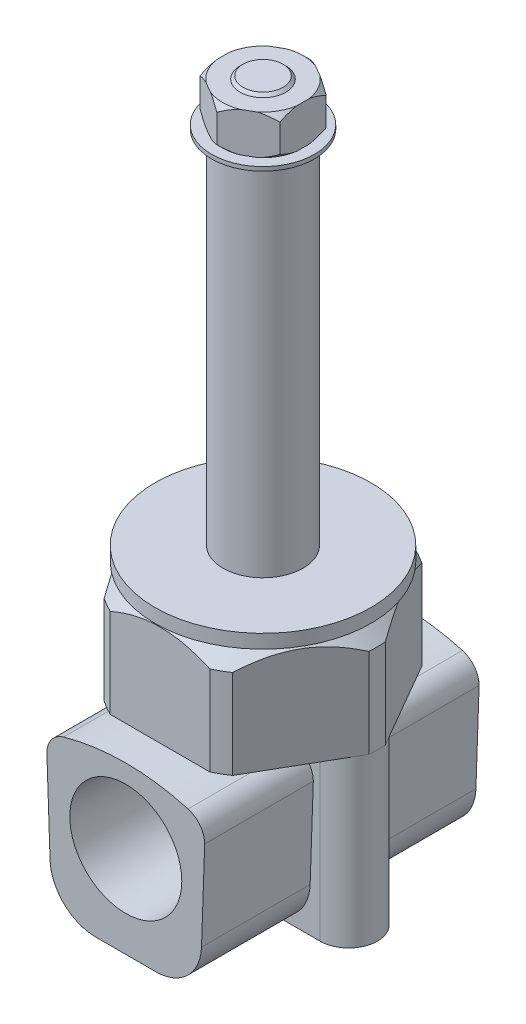
SolidWorks part; units mm, degrees
ref_plane "Front" through (0, 0, 0) normal (0, 0, 1) x (1, 0, 0)
ref_plane "Top" through (0, 0, 0) normal (0, 1, 0) x (1, 0, 0)
ref_plane "Right" through (0, 0, 0) normal (1, 0, 0) x (0, 0, -1)
sketch "Sketch1" plane through (0, 0, 0) normal (0, 1, 0) x (1, 0, 0)
  line L1 (-9.9737, -0.7251) -> (-5.6148, -8.2749)
  line L2 (-4.3589, -9) -> (4.3589, -9)
  line L3 (5.6148, -8.2749) -> (9.9737, -0.7251)
  line L4 (9.9737, 0.7251) -> (5.6148, 8.2749)
  line L5 (4.3589, 9) -> (-4.3589, 9)
  line L6 (-5.6148, 8.2749) -> (-9.9737, 0.7251)
  circle A0 centre (0, 0) radius 9 construction
  arc A1 (-4.3589, 9) -> (-5.6148, 8.2749) centre (0, 0) ccw
  arc A2 (-9.9737, 0.7251) -> (-9.9737, -0.7251) centre (0, 0) ccw
  arc A3 (-5.6148, -8.2749) -> (-4.3589, -9) centre (0, 0) ccw
  arc A4 (4.3589, -9) -> (5.6148, -8.2749) centre (0, 0) ccw
  arc A5 (9.9737, -0.7251) -> (9.9737, 0.7251) centre (0, 0) ccw
  arc A6 (5.6148, 8.2749) -> (4.3589, 9) centre (0, 0) ccw
  dimension "D1" = 18
  dimension "D2" = 20
extrude "Base Nut Extrude" add sketch "Sketch1" along normal blind 9.3
sketch "Sketch2" plane through (0, 0, 0) normal (0, 0, 1) x (1, 0, 0)
  line L0 (-9.9737, 9.3) -> (-5.6148, 9.3) construction
  line L1 (-9.9737, 9.3) -> (-10, 9.3) construction
  line L2 (-10, 9.3) -> (-10, 0) construction
  line L3 (-9.9737, 9.3) -> (-8.5, 9.3)
  line L4 (-9.9737, 9.3) -> (-10, 9.3)
  line L5 (-10, 9.3) -> (-10, 7.8)
  line L6 (-10, 7.8) -> (-8.5, 9.3)
  dimension "D1" = 1.5
  dimension "D2" = 1.5
ref_axis "Axis1" through (0, 49.0775, 0) along (0, -1, 0)
revolve "Nut Detail" cut sketch "Sketch2" angle 360 about axis through (0, 49.0775, 0) along (0, -1, 0)
sketch "Sketch3" plane through (0, 9.3, 0) normal (0, 1, 0) x (1, 0, 0)
  circle A0 centre (0, 0) radius 9.45
  dimension "D1" = 18.9
extrude "Coil Base" add sketch "Sketch3" along normal blind 1.2
sketch "Sketch4" plane through (0, 10.5, 0) normal (0, 1, 0) x (1, 0, 0)
  circle A0 centre (0, 0) radius 3.5
  dimension "D1" = 7
extrude "Inner Cylinder" add sketch "Sketch4" along normal blind 31.5
sketch "Sketch5" plane through (0, 42, 0) normal (0, 1, 0) x (1, 0, 0)
  circle A0 centre (0, 0) radius 4.5
  dimension "D1" = 9
extrude "Washer" add sketch "Sketch5" along normal blind 0.35
sketch "Sketch6" plane through (0, 42.35, 0) normal (0, 1, 0) x (1, 0, 0)
  circle A0 centre (0, 0) radius 2
  dimension "D1" = 4
extrude "Mounting Thread" add sketch "Sketch6" along normal blind 3.7
chamfer "Thread Chamfer" distance 0.25 1 edges at (0, 46.05, 2)
sketch "Sketch7" plane through (0, 0, 0) normal (0, -1, 0) x (1, 0, 0)
  line L0 (-7.5, 0) -> (7.5, 0) construction
  line L1 (-7.5, 2.5) -> (7.5, 2.5)
  line L3 (7.5, -2.5) -> (-7.5, -2.5)
  arc A0 (-7.5, 2.5) -> (-7.5, -2.5) centre (-7.5, 0) ccw
  arc A1 (7.5, -2.5) -> (7.5, 2.5) centre (7.5, 0) ccw
  point P4 (0, 0)
  dimension "D2" = 5
  dimension "D1" = 15
extrude "Port Base" add sketch "Sketch7" along normal blind 14.5
sketch "Sketch8" plane through (0, 0, 2.5) normal (0, 0, 1) x (1, 0, 0)
  line L0 (7.5, 0) -> (-7.5, 0) construction
  line L1 (-6.9, -2.6798) -> (-6.622, -10.6396)
  line L2 (-6.9, -2.6798) -> (-6.9, -10.5) construction
  line L3 (2.6245, -14.5) -> (-2.6245, -14.5)
  line L4 (6.9, -2.6798) -> (6.9, -10.5) construction
  line L5 (7.5, -14.5) -> (-7.5, -14.5) construction
  line L6 (6.9, -2.6798) -> (6.622, -10.6396)
  arc A0 (-6.622, -10.6396) -> (-2.6245, -14.5) centre (-2.6245, -10.5) ccw
  arc A1 (6.622, -10.6396) -> (2.6245, -14.5) centre (2.6245, -10.5) cw
  arc A2 (5.4444, -0.7553) -> (-5.4444, -0.7553) centre (0, -20) ccw
  arc A3 (-5.4444, -0.7553) -> (-6.9, -2.6798) centre (-4.9, -2.6798) ccw
  arc A4 (6.9, -2.6798) -> (5.4444, -0.7553) centre (4.9, -2.6798) ccw
  point P1 (0, 0)
  point P14 (6.9, -14.5)
  dimension "D2" = 2
  dimension "D3" = 40
  dimension "D4" = 4
  dimension "D5" = 2
  dimension "D6" = 4
  dimension "D1" = 13.8
extrude "In Port Body" add sketch "Sketch8" along normal blind 9.5 separate body
sketch "Sketch9" plane through (0, 0, -2.5) normal (0, 0, -1) x (-1, 0, 0)
  line L0 (6.9, -2.6798) -> (6.622, -10.6396) construction
  line L1 (-6.622, -10.6396) -> (-6.9, -2.6798) construction
  line L2 (7.5, -14.5) -> (-7.5, -14.5) construction
  line L3 (6.9, -2.6798) -> (6.622, -10.6396)
  line L4 (-6.622, -10.6396) -> (-6.9, -2.6798)
  line L5 (2.6245, -14.5) -> (-2.6245, -14.5)
  arc A0 (6.9, -2.6798) -> (5.4444, -0.7553) centre (4.9, -2.6798) ccw construction
  arc A1 (5.4444, -0.7553) -> (-5.4444, -0.7553) centre (0, -20) ccw construction
  arc A2 (-5.4444, -0.7553) -> (-6.9, -2.6798) centre (-4.9, -2.6798) ccw construction
  arc A3 (-6.622, -10.6396) -> (-2.6245, -14.5) centre (-2.6245, -10.5) ccw construction
  arc A4 (2.6245, -14.5) -> (6.622, -10.6396) centre (2.6245, -10.5) ccw construction
  arc A5 (6.9, -2.6798) -> (5.4444, -0.7553) centre (4.9, -2.6798) ccw
  arc A6 (5.4444, -0.7553) -> (-5.4444, -0.7553) centre (0, -20) ccw
  arc A7 (-5.4444, -0.7553) -> (-6.9, -2.6798) centre (-4.9, -2.6798) ccw
  arc A8 (-6.622, -10.6396) -> (-2.6245, -14.5) centre (-2.6245, -10.5) ccw
  arc A9 (2.6245, -14.5) -> (6.622, -10.6396) centre (2.6245, -10.5) ccw
extrude "Out Port Body" add sketch "Sketch9" along normal blind 9.5 separate body
hole_wizard "1/8 Rc In Port" positions "Sketch11" profile "Sketch10" size "1/8" standard "ISO"
sketch "Sketch11" plane through (0, 0, 12) normal (0, 0, 1) x (1, 0, 0)
  line L0 (-2.6245, -14.5) -> (2.6245, -14.5) construction
  point P0 (0, -6.5)
  dimension "D1" = 8
sketch "Sketch10" plane through (0, -6.5, 12) normal (1, 0, 0) x (0, -1, 0)
  line L0 (0, 0) -> (0, 9)
  line L1 (3.95, 9) -> (0, 9)
  line L2 (-3.95, 9) -> (0, 9) construction
  line L3 (3.95, 9) -> (3.95, 8.5)
  line L4 (3.95, 8.5) -> (4.633, 8.5)
  line L5 (4.633, 8.5) -> (4.8983, 0)
  line L6 (-4.633, 8.5) -> (-4.8983, 0) construction
  line L7 (4.8983, 0) -> (0, 0)
  line L8 (0, -6.35) -> (0, 107.95) construction
  line L11 (-3.95, 8.5) -> (-4.633, 8.5) construction
  dimension "Tap Drill Dia." = 7.9
  dimension "Tap Drill Depth" = 9
  dimension "Thread Dia." = 9.7967
  dimension "Thread Angle" = 3.576
  dimension "Thread Depth" = 8.5
  dimension "Drill Angle" = 180
hole_wizard "1/8 Rc Out Port" positions "Sketch13" profile "Sketch12" size "1/8" standard "ISO"
sketch "Sketch13" plane through (0, 0, -12) normal (0, 0, -1) x (-1, 0, 0)
  line L0 (7.5, -14.5) -> (-7.5, -14.5) construction
  point P0 (0, -6.5)
  dimension "D1" = 8
sketch "Sketch12" plane through (0, -6.5, -12) normal (1, 0, 0) x (0, 1, 0)
  line L0 (0, 0) -> (0, 12.8734)
  line L1 (3.95, 10.5) -> (0, 12.8734)
  line L2 (-3.95, 10.5) -> (0, 12.8734) construction
  line L3 (3.95, 10.5) -> (3.95, 7.4)
  line L4 (3.95, 7.4) -> (4.633, 7.4)
  line L5 (4.633, 7.4) -> (4.864, 0)
  line L6 (-4.633, 7.4) -> (-4.864, 0) construction
  line L7 (4.864, 0) -> (0, 0)
  line L8 (0, -6.35) -> (0, 107.95) construction
  line L11 (-3.95, 7.4) -> (-4.633, 7.4) construction
  dimension "Tap Drill Dia." = 7.9
  dimension "Tap Drill Depth" = 10.5
  dimension "Thread Dia." = 9.728
  dimension "Thread Angle" = 3.576
  dimension "Thread Depth" = 7.4
  dimension "Drill Angle" = 118
hole_wizard "M3 Mounting Holes" positions "Sketch15" profile "Sketch14" tap size "M3x0.5" standard "Ansi Metric"
sketch "Sketch15" plane through (0, -14.5, 0) normal (0, -1, 0) x (1, 0, 0)
  point P1 (7.5, 0)
  point P4 (-7.5, 0)
sketch "Sketch14" plane through (7.5, -14.5, 0) normal (1, 0, 0) x (0, 0, -1)
  line L0 (0, 0) -> (0, 5.7511)
  line L1 (0, 5.7511) -> (1.25, 5)
  line L2 (1.25, 5) -> (1.25, 0)
  line L5 (1.25, 0) -> (0, 0)
  line L10 (0, 5.7511) -> (-1.25, 5) construction
  line L11 (0, -6.35) -> (0, 107.95) construction
  dimension "Tap Drill Dia." = 2.5
  dimension "Tap Drill Depth" = 5
  dimension "Drill Angle" = 118
sketch "Sketch16" plane through (0, 0, 0) normal (0, -1, 0) x (1, 0, 0)
  line L0 (0, -10.75) -> (11, -10.75)
  arc A0 (10.7147, -0.8702) -> (-4.4256, 9.7968) centre (0, 0) ccw
  arc A1 (11, -10.75) -> (12.7619, -5.3219) centre (11, -7.75) ccw
  arc A2 (-9.3065, 10.2263) -> (-12.7619, 5.3219) centre (-11, 7.75) ccw
  arc A3 (-10.7147, 0.8702) -> (-12.7619, 5.3219) centre (-15.6983, 1.275) ccw
  arc A4 (-9.3065, 10.2263) -> (-4.4256, 9.7968) centre (-6.4839, 14.3534) ccw
  arc A5 (10.7147, -0.8702) -> (12.7619, -5.3219) centre (15.6983, -1.275) ccw
  arc A6 (-10.7147, 0.8702) -> (0, -10.75) centre (0, 0) ccw
  dimension "D1" = 21.5
  dimension "D3" = 10
  dimension "D4" = 11
  dimension "D2" = 6
  dimension "D5" = 7.75
  dimension "D6" = 11
extrude "33 Mount Base" [suppressed] add sketch "Sketch16" along normal blind 3
sketch "Sketch17" [suppressed] plane through (0, 0, 0) normal (0, 1, 0) x (1, 0, 0)
  circle A0 centre (-11, -7.75) radius 2.75
  circle A1 centre (11, 7.75) radius 2.75
  dimension "D1" = 5.5
extrude "33 Washer" [suppressed] add sketch "Sketch17" along normal blind 0.7
sketch "Sketch18" [suppressed] plane through (0, 0.7, 0) normal (0, 1, 0) x (1, 0, 0)
  circle A0 centre (11, 7.75) radius 2.75 construction
  circle A1 centre (-11, -7.75) radius 2.75 construction
  circle A2 centre (11, 7.75) radius 2.75
  circle A3 centre (-11, -7.75) radius 2.75
extrude "Screw Head" [suppressed] add sketch "Sketch18" along normal blind 2 separate body
sketch "Sketch19" [suppressed] plane through (0, 2.7, 0) normal (0, 1, 0) x (1, 0, 0)
  line L0 (11, 10.5) -> (11, 5) construction
  line L1 (10.7, 10.4836) -> (10.7, 5.0164)
  line L2 (-11, -5) -> (-11, -10.5) construction
  line L3 (-11.3, -5.0164) -> (-11.3, -10.4836)
  line L4 (-10.7, -5.0164) -> (-10.7, -10.4836)
  line L5 (-11.3, -5) -> (-11.3, -10.5) construction
  line L6 (-10.7, -5) -> (-10.7, -10.5) construction
  line L7 (11.3, 10.4836) -> (11.3, 5.0164)
  line L8 (11.3, 10.5) -> (11.3, 5) construction
  line L9 (10.7, 10.5) -> (10.7, 5) construction
  circle A0 centre (-11, -7.75) radius 2.75 construction
  circle A1 centre (-11, -7.75) radius 2.75 construction
  arc A2 (-10.7, -5.0164) -> (-11.3, -5.0164) centre (-11, -7.75) ccw
  arc A3 (-11.3, -10.4836) -> (-10.7, -10.4836) centre (-11, -7.75) ccw
  circle A4 centre (11, 7.75) radius 2.75 construction
  circle A5 centre (11, 7.75) radius 2.75 construction
  arc A6 (10.7, 5.0164) -> (11.3, 5.0164) centre (11, 7.75) ccw
  arc A7 (11.3, 10.4836) -> (10.7, 10.4836) centre (11, 7.75) ccw
  dimension "D1" = 0.3
  dimension "D2" = 0.3
  dimension "D3" = 0.3
  dimension "D4" = 0.3
extrude "Slot Cut" [suppressed] cut sketch "Sketch19" against normal blind 0.8
fillet "Head Fillet 1" [suppressed] radius 0.5
fillet "Head Fillet 2" [suppressed] radius 0.5
sketch "Sketch20" [suppressed] plane through (0, -3, 0) normal (0, -1, 0) x (1, 0, 0)
  circle A0 centre (-11, 7.75) radius 1.5
  circle A1 centre (11, -7.75) radius 1.5
  dimension "D1" = 3
extrude "Screw Body" [suppressed] add sketch "Sketch20" along normal blind 4
chamfer "Screw Body Chamfer" [suppressed] distance 0.5
sketch "Sketch21" plane through (0, 42.35, 0) normal (0, 1, 0) x (1, 0, 0)
  line L1 (-3.5, 2.0207) -> (-3.5, -2.0207)
  line L2 (-3.5, -2.0207) -> (0, -4.0415)
  line L3 (0, -4.0415) -> (3.5, -2.0207)
  line L4 (3.5, -2.0207) -> (3.5, 2.0207)
  line L5 (3.5, 2.0207) -> (0, 4.0415)
  line L6 (0, 4.0415) -> (-3.5, 2.0207)
  circle A0 centre (0, 0) radius 2 construction
  circle A1 centre (0, 0) radius 2
  circle A2 centre (0, 0) radius 3.5 construction
  dimension "D1" = 7
extrude "Hex Nut" add sketch "Sketch21" along normal blind 3.45
sketch "Sketch23" plane through (0, 0, 0) normal (1, 0, 0) x (0, 0, -1)
  line L0 (-4.0415, 42.35) -> (-2.0207, 42.35) construction
  line L1 (-4.0415, 45.8) -> (-2.0207, 45.8) construction
  line L2 (-4.0415, 45.8) -> (-4.0415, 42.35) construction
  line L3 (-4.0415, 42.35) -> (-3.5415, 42.35)
  line L4 (-4.0415, 45.8) -> (-3.5415, 45.8)
  line L5 (-4.0415, 45.8) -> (-4.0415, 45.3)
  line L6 (-4.0415, 45.3) -> (-3.5415, 45.8)
  line L7 (-4.0415, 42.85) -> (-3.5415, 42.35)
  line L8 (-4.0415, 42.85) -> (-4.0415, 42.35)
  dimension "D1" = 0.5
  dimension "D2" = 0.5
  dimension "D3" = 0.5
  dimension "D4" = 0.5
revolve "Hex Nut Detail" cut sketch "Sketch23" angle 360 about axis through (0, 49.0775, 0) along (0, -1, 0)
